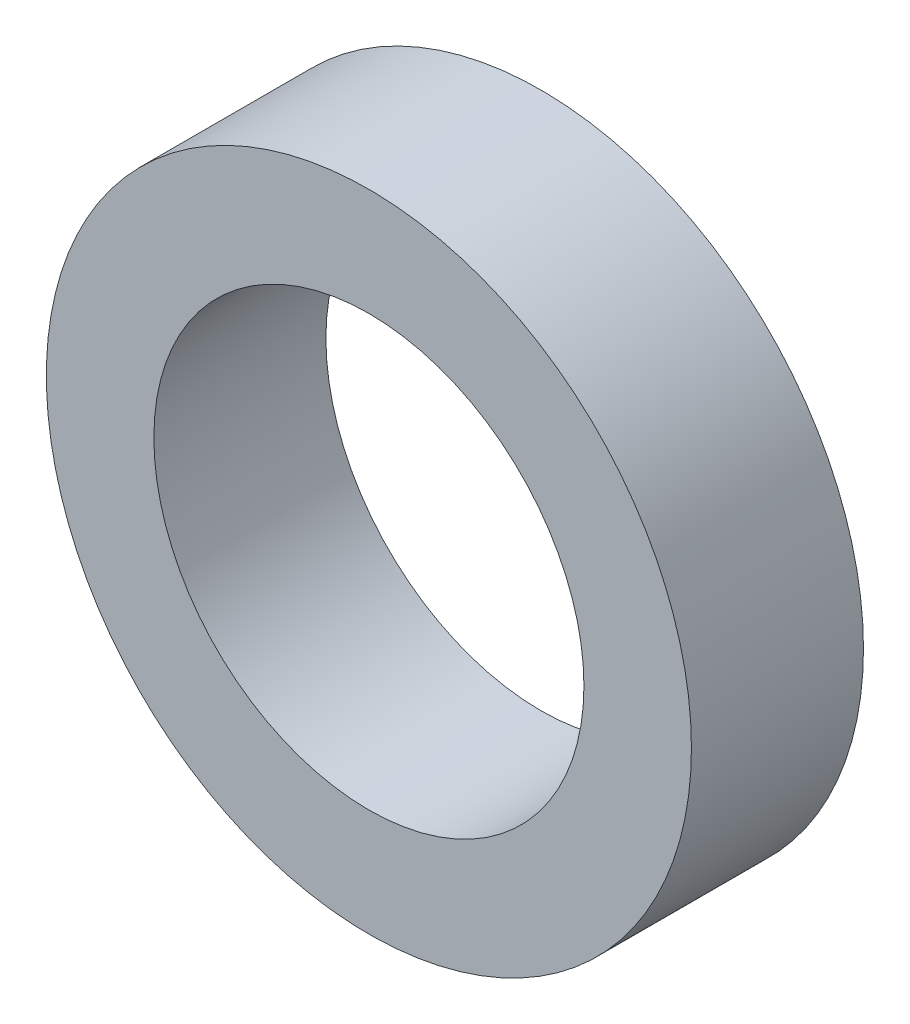
SolidWorks part; units mm, degrees
material "AISI 304"
ref_plane "正面" through (0, 0, 0) normal (0, 0, 1) x (1, 0, 0)
ref_plane "平面" through (0, 0, 0) normal (0, 1, 0) x (1, 0, 0)
ref_plane "右側面" through (0, 0, 0) normal (1, 0, 0) x (0, 0, -1)
sketch "ｽｹｯﾁ1" plane through (0, 0, 0) normal (0, 0, 1) x (1, 0, 0)
  circle A0 centre (0, 0) radius 5
  circle A1 centre (0, 0) radius 7.5
  dimension "D1" = 10
  dimension "D2" = 15
extrude "ﾎﾞｽ - 押し出し1" add sketch "ｽｹｯﾁ1" along normal blind 4
